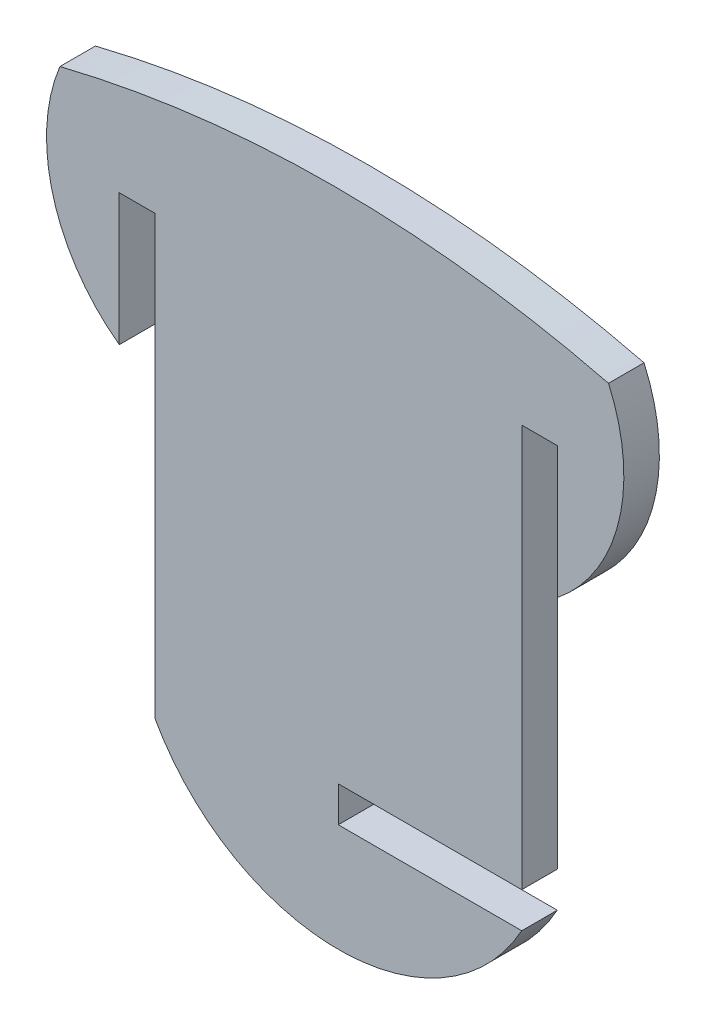
SolidWorks part; units mm, degrees
ref_plane "Front" through (0, 0, 0) normal (0, 0, 1) x (1, 0, 0)
ref_plane "Top" through (0, 0, 0) normal (0, 1, 0) x (1, 0, 0)
ref_plane "Right" through (0, 0, 0) normal (1, 0, 0) x (0, 0, -1)
sketch "Sketch1" plane through (0, 0, 0) normal (0, 0, 1) x (1, 0, 0)
  line L0 (327.4345, 72.7612) -> (327.4345, 61.6388)
  line L1 (324.4345, 72.7612) -> (324.4345, 38.7732)
  line L2 (290.4345, 72.7612) -> (290.4345, 61.6388)
  line L3 (293.4345, 72.7612) -> (293.4345, 35.8472)
  line L4 (324.4345, 38.7732) -> (308.9345, 38.7732)
  line L5 (308.9345, 38.7732) -> (308.9345, 35.7732)
  line L6 (308.9345, 35.7732) -> (324.4345, 35.7732)
  line L7 (290.4345, 72.7612) -> (293.4345, 72.7612)
  line L8 (327.4345, 72.7612) -> (324.4345, 72.7612)
  arc A0 (327.4345, 61.6388) -> (331.7619, 79.4821) centre (318.0124, 73.3703) ccw
  arc A1 (285.4218, 79.4844) -> (290.4345, 61.6388) centre (299.34, 73.7671) ccw
  arc A3 (331.7619, 79.4821) -> (285.4218, 79.4844) centre (308.5874, -13.9268) ccw
  arc A4 (293.4345, 35.8472) -> (324.4345, 35.7732) centre (308.9549, 44.351) ccw
  dimension "D6" = 15.5
  dimension "D1" = 3
  dimension "D2" = 3
  dimension "D3" = 3
  dimension "D4" = 31
  dimension "D5" = 15.5
extrude "Base-Extrude" add sketch "Sketch1" along normal blind 3
